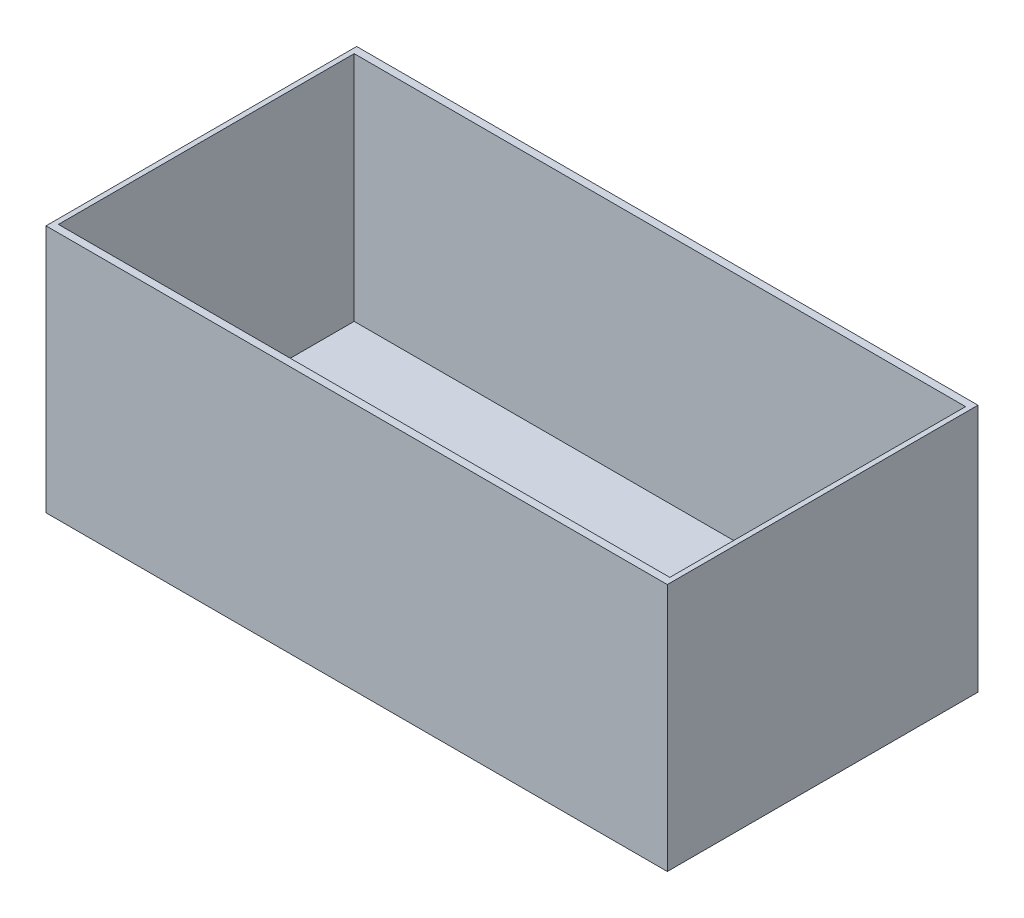
SolidWorks part; units mm, degrees
ref_plane "Front Plane" through (0, 0, 0) normal (0, 0, 1) x (1, 0, 0)
ref_plane "Top Plane" through (0, 0, 0) normal (0, 1, 0) x (1, 0, 0)
ref_plane "Right Plane" through (0, 0, 0) normal (1, 0, 0) x (0, 0, -1)
sketch "Sketch1" plane through (0, 0, 0) normal (0, 1, 0) x (1, 0, 0)
  line L1 (-112.1121, 55.9309) -> (2387.8879, 55.9309)
  line L2 (-112.1121, 55.9309) -> (-112.1121, -1194.0691)
  line L3 (-112.1121, -1194.0691) -> (2387.8879, -1194.0691)
  line L4 (2387.8879, 55.9309) -> (2387.8879, -1194.0691)
  dimension "D1" = 2500
  dimension "D2" = 1250
extrude "Boss-Extrude1" add sketch "Sketch1" along normal blind 1000
sketch "Sketch4" plane through (0, 1000, 0) normal (0, 1, 0) x (1, 0, 0)
  line L0 (2387.8879, 55.9309) -> (-112.1121, 55.9309) construction
  line L1 (-92.1121, 25.9309) -> (2367.8879, 25.9309)
  line L2 (-92.1121, 25.9309) -> (-92.1121, -1164.0691)
  line L3 (-92.1121, -1164.0691) -> (2367.8879, -1164.0691)
  line L4 (2367.8879, 25.9309) -> (2367.8879, -1164.0691)
  line L5 (2387.8879, -1194.0691) -> (2387.8879, 55.9309) construction
  line L6 (-112.1121, 55.9309) -> (-112.1121, -1194.0691) construction
  line L7 (-112.1121, -1194.0691) -> (2387.8879, -1194.0691) construction
  dimension "D1" = 30
  dimension "D2" = 20
  dimension "D3" = 20
  dimension "D4" = 30
extrude "Cut-Extrude2" cut sketch "Sketch4" against normal blind 933
